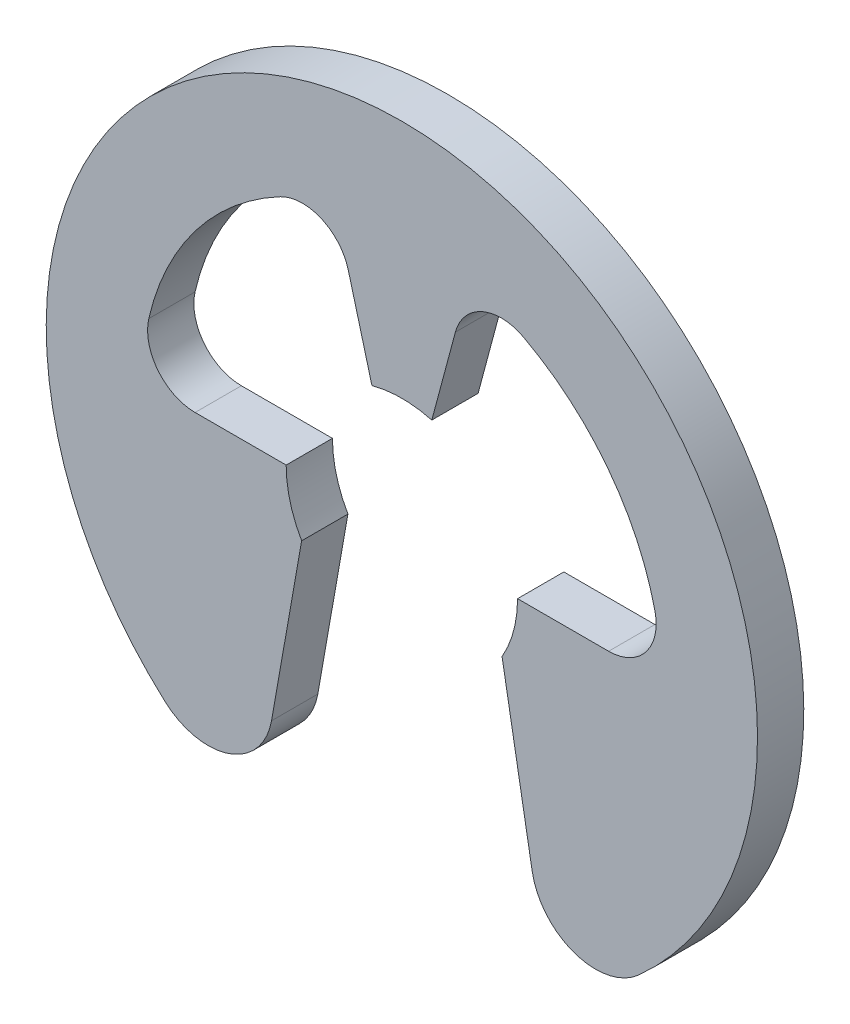
SolidWorks part; units mm, degrees
ref_plane "Plane1" through (0, 0, 0) normal (0, 0, 1) x (1, 0, 0)
ref_plane "Plane2" through (0, 0, 0) normal (0, 1, 0) x (1, 0, 0)
ref_plane "Plane3" through (0, 0, 0) normal (1, 0, 0) x (0, 0, -1)
sketch "Clipboard" plane through (0, 0, 0) normal (0, 0, 1) x (1, 0, 0)
  line L0 (0, 0) -> (1.3168, 0)
  circle A0 centre (0, 0) radius 1.5494
  circle A1 centre (0, 0) radius 4.7625
  dimension "FreeID" = 3.0988
  dimension "FreeOD" = 9.525
  dimension "Bridge" = 1.3168
sketch "BodySke" plane through (0, 0, 0) normal (0, 0, 1) x (1, 0, 0)
  line L0 (-0.7581, 0) -> (0.7581, 0) construction
  line L1 (0, 0) -> (0, 1.5875) construction
  line L2 (0, 0) -> (0.1962, 0.7323) construction
  line L3 (0, 0) -> (1.3748, -0.7938) construction
  line L4 (0, 0) -> (-0.1962, 0.7323) construction
  line L5 (0, 0) -> (-1.3748, -0.7938) construction
  line L6 (1.3748, -0.7938) -> (1.7884, -3.1394)
  line L7 (-1.3748, -0.7938) -> (-1.7884, -3.1394)
  line L9 (1.5875, 0) -> (2.837, 0)
  line L10 (-1.5875, 0) -> (-2.837, 0)
  line L11 (0.4109, 1.5334) -> (0.7343, 2.7403)
  line L12 (-0.4109, 1.5334) -> (-0.7343, 2.7403)
  circle A0 centre (0, 0) radius 1.5875 construction
  arc A1 (3.4723, 0.7978) -> (1.6693, 3.1475) centre (0, 0) ccw
  arc A2 (3.2438, -3.6453) -> (-3.2438, -3.6453) centre (0, 0) ccw
  arc A3 (1.3748, -0.7938) -> (1.5875, 0) centre (0, 0) ccw
  arc A4 (-1.6693, 3.1475) -> (-3.4723, 0.7978) centre (0, 0) ccw
  arc A5 (-1.5875, 0) -> (-1.3748, -0.7938) centre (0, 0) ccw
  arc A6 (-0.4109, 1.5334) -> (0.4109, 1.5334) centre (0, 0) cw
  arc A7 (1.6693, 3.1475) -> (0.7343, 2.7403) centre (1.3639, 2.5716) ccw
  arc A8 (1.7884, -3.1394) -> (3.2438, -3.6453) centre (2.6573, -2.9862) ccw
  arc A9 (-3.2438, -3.6453) -> (-1.7884, -3.1394) centre (-2.6573, -2.9862) ccw
  arc A10 (-3.4723, 0.7978) -> (-2.837, 0) centre (-2.837, 0.6518) ccw
  arc A11 (-0.7343, 2.7403) -> (-1.6693, 3.1475) centre (-1.3639, 2.5716) ccw
  arc A12 (2.837, 0) -> (3.4723, 0.7978) centre (2.837, 0.6518) ccw
  dimension "D1" = 30
  dimension "GrooveDia" = 3.175
  dimension "OutsideDia" = 9.7592
  dimension "D3" = 30
  dimension "TipRad" = 0.8823
  dimension "CavityDia" = 7.1255
  dimension "CavityFilletRad" = 0.6518
  dimension "D4" = 20
extrude "Body" add sketch "BodySke" against normal blind 0.635
equation "' \"FreeID@Clipboard\" = 0.025"
equation "' \"Thickness@Body\" = 0.01"
equation "' \"GrooveDia@BodySke\" = 0.026"
equation "' \"FreeOD@Clipboard\" = 0.079"
equation "' \"FreeID@Clipboard\" = 1.213"
equation "' \"Thickness@Body\" = 0.062"
equation "' \"GrooveDia@BodySke\" = 1.23"
equation "' \"FreeOD@Clipboard\" = 1.875"
equation "\"OutsideDia@BodySke\" = ( \"GrooveDia@BodySke\"  /  \"FreeID@Clipboard\" )  * \"FreeOD@Clipboard\""
equation "\"Bridge@Clipboard\" =  (\"OutsideDia@BodySke\" - \"GrooveDia@BodySke\") / 2 * 0.4"
equation "\"CavityDia@BodySke\" = \"OutsideDia@BodySke\"  - 2 * \"Bridge@Clipboard\""
equation "\"CavityFilletRad@BodySke\" =  (\"CavityDia@BodySke\" - \"GrooveDia@BodySke\") / 2 * 0.33"
equation "\"TipRad@BodySke\" = 0.67 * \"Bridge@Clipboard\""
